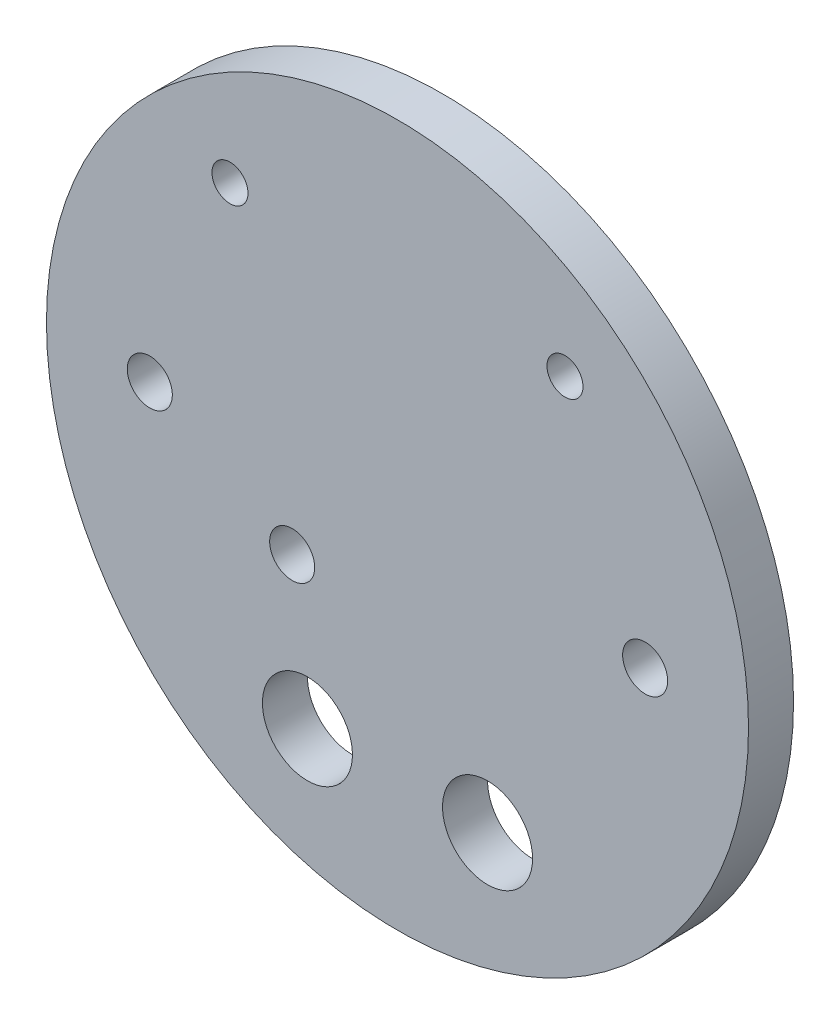
SolidWorks part; units mm, degrees
ref_plane "Front Plane" through (0, 0, 0) normal (0, 0, 1) x (1, 0, 0)
ref_plane "Top Plane" through (0, 0, 0) normal (0, 1, 0) x (1, 0, 0)
ref_plane "Right Plane" through (0, 0, 0) normal (1, 0, 0) x (0, 0, -1)
sketch "Sketch1" plane through (0, 0, 0) normal (0, 0, 1) x (1, 0, 0)
  circle A0 centre (0, 0) radius 49.5046
  dimension "D1" = 99.0092
extrude "Boss-Extrude1" add sketch "Sketch1" along normal blind 3.175
sketch "Sketch2" plane through (0, 0, 3.175) normal (0, 0, 1) x (1, 0, 0)
  circle A0 centre (0, 0) radius 47.6885
  dimension "D1" = 95.377
extrude "Boss-Extrude2" add sketch "Sketch2" along normal blind 3.175
sketch "Sketch3" plane through (0, 0, 6.35) normal (0, 0, 1) x (1, 0, 0)
  circle A0 centre (-12.7, -31.2354) radius 6.35
  circle A1 centre (12.7, -31.2354) radius 6.35
  circle A2 centre (-12.7, -31.2354) radius 12.7 construction
  circle A3 centre (12.7, -31.2354) radius 12.7 construction
  circle A4 centre (12.7, -31.2354) radius 13.97 construction
  circle A5 centre (-12.7, -31.2354) radius 13.97 construction
  circle A6 centre (0, 0) radius 47.6885 construction
  circle A7 centre (-34.925, 0) radius 3.175
  circle A8 centre (34.925, 0) radius 3.175
  circle A9 centre (0, 6.35) radius 15.24 construction
  circle A10 centre (-14.8504, -11.0295) radius 8.89 construction
  circle A11 centre (0, 6.35) radius 16.51 construction
  circle A12 centre (-14.8504, -11.0295) radius 7.62 construction
  circle A13 centre (0, 6.35) radius 11.1125
  circle A14 centre (-14.8504, -11.0295) radius 3.175
  circle A15 centre (-23.622, 29.972) radius 2.54
  circle A16 centre (23.622, 29.972) radius 2.54
  circle A17 centre (23.622, -17.272) radius 2.54
  circle A18 centre (-23.622, -17.272) radius 2.54
  dimension "D1" = 12.7
  dimension "D2" = 12.7
  dimension "D3" = 27.94
  dimension "D4" = 27.94
  dimension "D5" = 25.4
  dimension "D6" = 25.4
  dimension "D7" = 6.35
  dimension "D8" = 6.35
  dimension "D11" = 30.48
  dimension "D12" = 33.02
  dimension "D13" = 15.24
  dimension "D14" = 17.78
  dimension "D15" = 22.225
  dimension "D16" = 6.35
  dimension "D18" = 5.08
  dimension "D9" = 69.85
  dimension "D10" = 34.925
  dimension "D17" = 6.35
  dimension "D19" = 47.244
  dimension "D20" = 47.244
  dimension "D21" = 23.622
  dimension "D22" = 23.622
extrude "Cut-Extrude1" cut sketch "Sketch3" against normal through all
sketch "Sketch4" plane through (0, 0, 6.35) normal (0, 0, 1) x (1, 0, 0)
  circle A0 centre (0, 0) radius 49.5046
  circle A1 centre (0, 0) radius 47.6885
extrude "Boss-Extrude3" add sketch "Sketch4" against normal up to surface (3.175 mm away) up to face at (47.6885, 0, 3.175)
sketch "Sketch5" plane through (0, 0, 6.35) normal (0, 0, 1) x (1, 0, 0)
  circle A0 centre (0, 6.35) radius 11.1125
extrude "Boss-Extrude4" add sketch "Sketch5" against normal up to surface (6.35 mm away) up to face at (-21.082, -17.272, 0)
sketch "Sketch6" plane through (0, 0, 6.35) normal (0, 0, 1) x (1, 0, 0)
  circle A0 centre (-23.622, -17.272) radius 2.54
  circle A1 centre (23.622, -17.272) radius 2.54
extrude "Boss-Extrude5" add sketch "Sketch6" against normal blind 6.35
